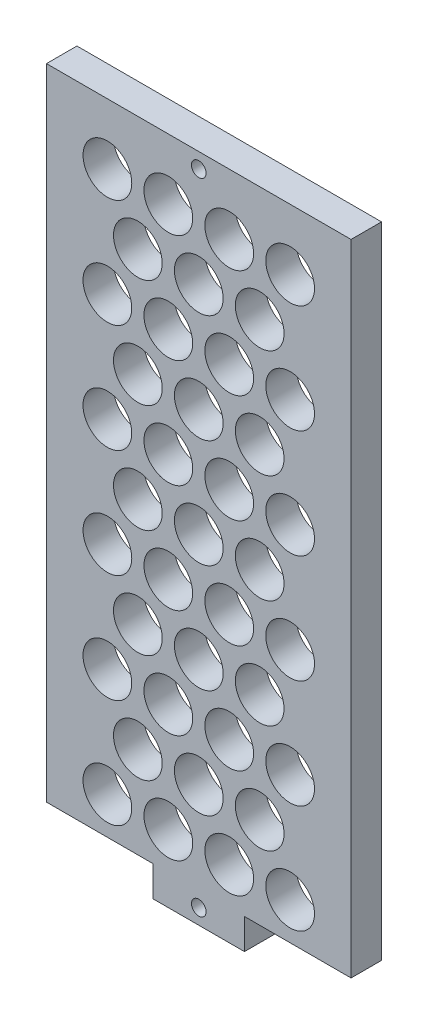
SolidWorks part; units mm, degrees
ref_plane "Front Plane" through (0, 0, 0) normal (0, 0, 1) x (1, 0, 0)
ref_plane "Top Plane" through (0, 0, 0) normal (0, 1, 0) x (1, 0, 0)
ref_plane "Right Plane" through (0, 0, 0) normal (1, 0, 0) x (0, 0, -1)
sketch "Sketch1" plane through (0, 0, 0) normal (0, 0, 1) x (1, 0, 0)
  line L1 (0, 0) -> (50.8, 0)
  line L2 (0, 0) -> (0, 127)
  line L3 (0, 127) -> (50.8, 127)
  line L4 (50.8, 0) -> (50.8, 127)
  dimension "D1" = 127
  dimension "D2" = 50.8
extrude "Boss-Extrude1" add sketch "Sketch1" along normal blind 6.35
sketch "Sketch2" plane through (0, 0, 6.35) normal (0, 0, 1) x (1, 0, 0)
  line L0 (50.8, 127) -> (0, 127) construction
  line L1 (6.35, 98.0722) -> (44.45, 98.0722) construction
  line L2 (6.35, 75.4944) -> (44.45, 75.4944) construction
  line L3 (25.4, 28.9278) -> (25.4, 54.3278) construction
  line L4 (0, -3.4925) -> (0, 3.4925) construction
  line L5 (6.35, 52.9167) -> (44.45, 52.9167) construction
  line L6 (6.35, 30.3389) -> (44.45, 30.3389) construction
  line L7 (0, 109.3611) -> (50.8, 109.3611) construction
  line L8 (50.8, 0) -> (50.8, 127) construction
  line L9 (25.4, 122.0611) -> (25.4, 96.6611) construction
  line L10 (6.35, 120.65) -> (19.05, 120.65) construction
  line L11 (19.05, 120.65) -> (31.75, 120.65) construction
  line L12 (31.75, 120.65) -> (44.45, 120.65) construction
  line L13 (44.45, 120.65) -> (31.75, 120.65) construction
  line L14 (6.35, 120.65) -> (0, 120.65) construction
  line L15 (12.7, 109.3611) -> (25.4, 109.3611) construction
  line L16 (38.1, 109.3611) -> (25.4, 109.3611) construction
  line L17 (38.1, 120.65) -> (38.1, 109.3611) construction
  line L18 (6.35, 7.7611) -> (44.45, 7.7611) construction
  line L19 (25.4, 31.75) -> (25.4, 6.35) construction
  circle A0 centre (6.35, 98.0722) radius 5.08
  circle A1 centre (19.05, 98.0722) radius 5.08
  circle A2 centre (31.75, 98.0722) radius 5.08
  circle A3 centre (44.45, 98.0722) radius 5.08
  circle A4 centre (12.7, 86.7833) radius 5.08
  circle A5 centre (25.4, 86.7833) radius 5.08
  circle A6 centre (38.1, 86.7833) radius 5.08
  circle A7 centre (44.45, 75.4944) radius 5.08
  circle A8 centre (31.75, 75.4944) radius 5.08
  circle A9 centre (19.05, 75.4944) radius 5.08
  circle A10 centre (6.35, 75.4944) radius 5.08
  circle A11 centre (6.35, 30.3389) radius 5.08
  circle A12 centre (19.05, 30.3389) radius 5.08
  circle A13 centre (31.75, 30.3389) radius 5.08
  circle A14 centre (19.05, 120.65) radius 5.08
  circle A15 centre (6.35, 120.65) radius 5.08
  circle A16 centre (31.75, 120.65) radius 5.08
  circle A17 centre (44.45, 120.65) radius 5.08
  circle A18 centre (25.4, 109.3611) radius 5.08
  circle A19 centre (38.1, 109.3611) radius 5.08
  circle A20 centre (12.7, 109.3611) radius 5.08
  circle A21 centre (44.45, 30.3389) radius 5.08
  circle A22 centre (38.1, 41.6278) radius 5.08
  circle A23 centre (25.4, 41.6278) radius 5.08
  circle A24 centre (12.7, 41.6278) radius 5.08
  circle A25 centre (38.1, 64.2056) radius 5.08
  circle A26 centre (25.4, 64.2056) radius 5.08
  circle A27 centre (12.7, 64.2056) radius 5.08
  circle A28 centre (44.45, 52.9167) radius 5.08
  circle A29 centre (31.75, 52.9167) radius 5.08
  circle A30 centre (19.05, 52.9167) radius 5.08
  circle A31 centre (6.35, 52.9167) radius 5.08
  circle A32 centre (12.7, 19.05) radius 5.08
  circle A33 centre (25.4, 19.05) radius 5.08
  circle A34 centre (38.1, 19.05) radius 5.08
  circle A35 centre (6.35, 7.7611) radius 5.08
  circle A36 centre (19.05, 7.7611) radius 5.08
  circle A37 centre (31.75, 7.7611) radius 5.08
  circle A38 centre (44.45, 7.7611) radius 5.08
  point P46 (25.4, 109.3611)
  point P55 (25.4, 120.65)
  point P56 (25.4, 120.65)
  point P57 (1.27, 120.65)
  point P59 (24.13, 120.65)
  point P66 (12.7, 120.65)
  dimension "D13" = 10.16
  dimension "D19" = 10.16
  dimension "D2" = 25.4
  dimension "D3" = 6.35
  dimension "D4" = 11.2889
  dimension "D16" = 6.35
  dimension "D17" = 2.54
  dimension "D18" = 1.27
extrude "Cut-Extrude1" cut sketch "Sketch2" against normal through all
sketch "Sketch3" plane through (0, 0, 6.35) normal (0, 0, 1) x (1, 0, 0)
  line L0 (3.4925, 0) -> (-3.4925, 0) construction
  line L1 (15.875, 0) -> (34.925, 0)
  line L2 (15.875, 0) -> (15.875, -6.35)
  line L3 (15.875, -6.35) -> (34.925, -6.35)
  line L4 (34.925, 0) -> (34.925, -6.35)
  line L5 (0, -3.4925) -> (0, 3.4925) construction
  line L6 (15.875, -3.175) -> (34.925, -3.175) construction
  circle A0 centre (25.4, -3.175) radius 1.524
  dimension "D4" = 3.048
  dimension "D1" = 19.05
  dimension "D2" = 15.875
  dimension "D3" = 6.35
extrude "Boss-Extrude2" add sketch "Sketch3" against normal blind 6.35 separate body
sketch "Sketch4" plane through (0, 0, 6.35) normal (0, 0, 1) x (1, 0, 0)
  line L3 (50.8, 127) -> (50.8, 0)
  line L4 (50.8, 0) -> (57.15, 0)
  line L5 (57.15, 130.175) -> (57.15, 0)
  line L6 (0, 0) -> (-6.35, 0)
  line L7 (0, 0) -> (0, 127)
  line L9 (-6.35, 0) -> (-6.35, 127)
  line L10 (0, 127) -> (50.8, 127)
  line L11 (-6.35, 127) -> (-6.35, 133.35)
  line L12 (-6.35, 133.35) -> (57.15, 133.35)
  line L13 (57.15, 130.175) -> (57.15, 133.35)
  dimension "D1" = 6.35
  dimension "1/4" = 6.35
  dimension "D3" = 3.175
  dimension "D4" = 6.35
extrude "Boss-Extrude3" add sketch "Sketch4" against normal blind 6.35
sketch "Sketch5" plane through (0, 0, 6.35) normal (0, 0, 1) x (1, 0, 0)
  line L0 (-6.35, 130.175) -> (57.15, 130.175) construction
  line L1 (-6.35, 133.35) -> (-6.35, 0) construction
  line L2 (57.15, 0) -> (57.15, 133.35) construction
  line L3 (57.15, 133.35) -> (-6.35, 133.35) construction
  circle A0 centre (25.4, 130.175) radius 1.524
  dimension "D2" = 3.048
  dimension "D1" = 3.175
extrude "Cut-Extrude2" cut sketch "Sketch5" against normal through all
equation "\"0.005`in\"=0.01"
